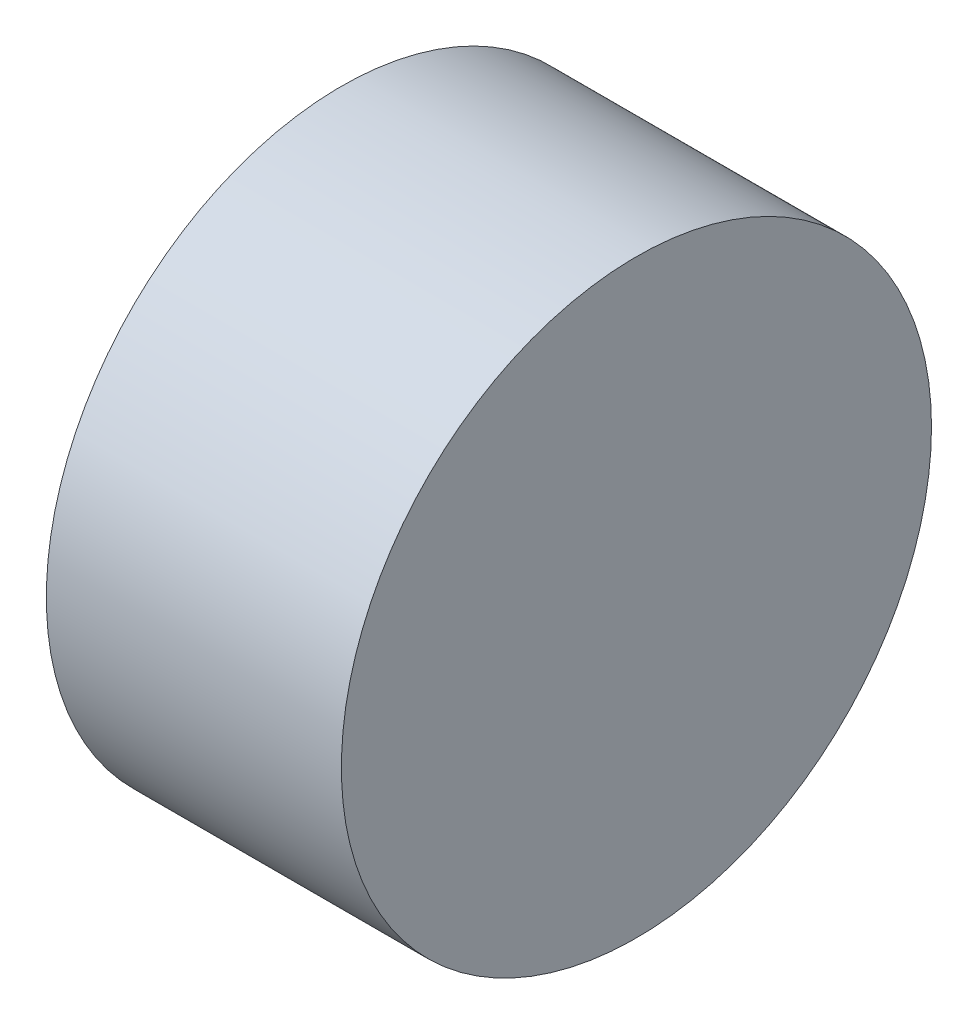
SolidWorks part; units mm, degrees
material "Rubber"
ref_plane "Front Plane" through (0, 0, 0) normal (0, 0, 1) x (1, 0, 0)
ref_plane "Top Plane" through (0, 0, 0) normal (0, 1, 0) x (1, 0, 0)
ref_plane "Right Plane" through (0, 0, 0) normal (1, 0, 0) x (0, 0, -1)
sketch "Sketch1" plane through (0, 0, 0) normal (1, 0, 0) x (0, 0, -1)
  circle A0 centre (0, 0) radius 30
  circle A1 centre (0, 0) radius 2.5
  dimension "D1" = 60
  dimension "D2" = 5
extrude "Boss-Extrude1" add sketch "Sketch1" along normal blind 10
sketch "Sketch2" plane through (10, 0, 0) normal (1, 0, 0) x (0, 0, -1)
  circle A0 centre (0, 0) radius 30
  circle A3 centre (0, 0) radius 30 construction
extrude "Boss-Extrude2" add sketch "Sketch2" along normal blind 20
